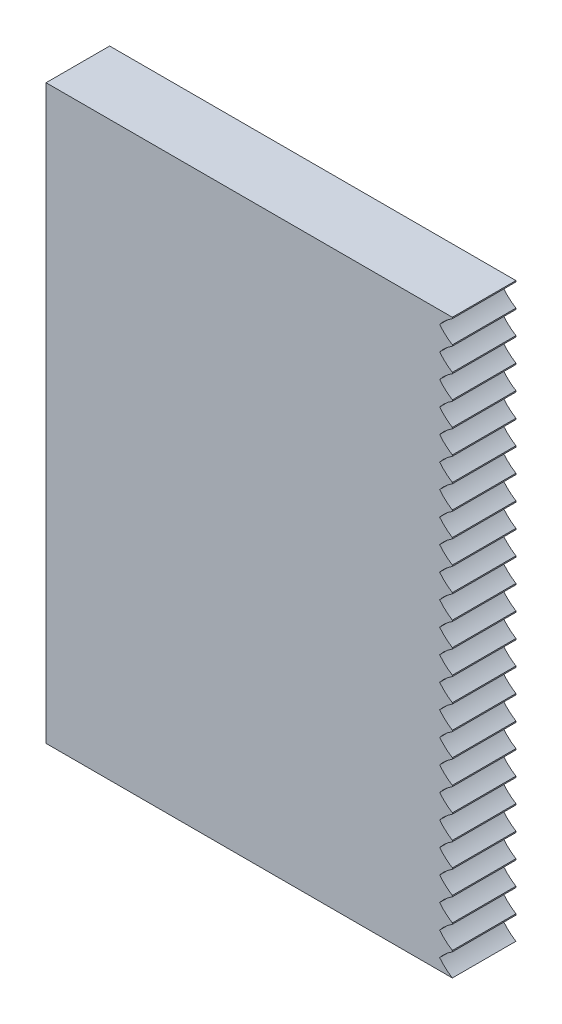
SolidWorks part; units mm, degrees
ref_plane "정면" through (0, 0, 0) normal (0, 0, 1) x (1, 0, 0)
ref_plane "윗면" through (0, 0, 0) normal (0, 1, 0) x (1, 0, 0)
ref_plane "우측면" through (0, 0, 0) normal (1, 0, 0) x (0, 0, -1)
sketch "스케치1" plane through (0, 0, 0) normal (0, 0, 1) x (1, 0, 0)
  line L1 (0, 0) -> (31.95, 0)
  line L2 (0, 0) -> (0, 45)
  line L3 (0, 45) -> (31.95, 45)
  line L4 (31.95, 0) -> (31.95, 45)
  line L6 (32, -22.1293) -> (32, 47.4465) construction
  line L7 (32, -5.804) -> (32, -15.804) construction
  dimension "D1" = 0.1
  dimension "D2" = 45
extrude "보스-돌출1" add sketch "스케치1" along normal blind 5
sketch "스케치2" plane through (0, 0, 5) normal (0, 0, 1) x (1, 0, 0)
  line L0 (42.95, 0.8896) -> (30.95, 0.8896) construction
  line L1 (42.95, 0.8896) -> (42.95, 36.5636) construction
  line L3 (42.95, 2.3896) -> (34.0759, 2.3896) construction
  line L5 (34.0759, 2.3896) -> (34.0759, -0.6104)
  line L7 (31.95, 0) -> (31.95, 45) construction
  circle A3 centre (42.95, 0.8896) radius 9 construction
  arc A4 (34.0759, 2.3896) -> (30.95, 0.8896) centre (34.0759, -1.6175) ccw
  arc A5 (34.0759, -0.6104) -> (30.95, 0.8896) centre (34.0759, 3.3966) cw
  dimension "D2" = 18
  dimension "D4" = 11
  dimension "D3" = 12
  dimension "D1" = 1.5
extrude "컷-돌출1" cut sketch "스케치2" against normal through all
pattern_linear "선형 패턴1" count 24 spacing 1.875 along (0, 1, 0) of "컷-돌출1"
